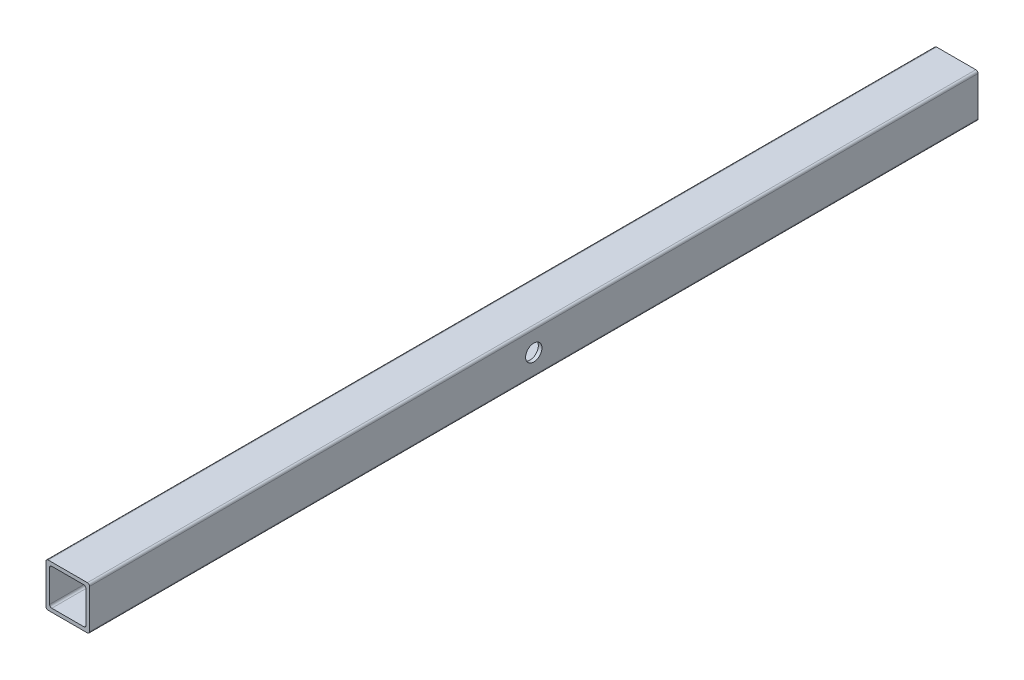
SolidWorks part; units mm, degrees
ref_plane "Front Plane" through (0, 0, 0) normal (0, 0, 1) x (1, 0, 0)
ref_plane "Top Plane" through (0, 0, 0) normal (0, 1, 0) x (1, 0, 0)
ref_plane "Right Plane" through (0, 0, 0) normal (1, 0, 0) x (0, 0, -1)
sketch "Sketch1" plane through (0, 0, 0) normal (0, 0, 1) x (1, 0, 0)
  line L1 (1.27, 0) -> (19.9136, 0)
  line L2 (0, 1.27) -> (0, 19.9136)
  line L3 (1.27, 21.1836) -> (19.9136, 21.1836)
  line L4 (21.1836, 1.27) -> (21.1836, 19.9136)
  line L5 (-0.8382, 23.2918) -> (22.0218, 23.2918)
  line L6 (-2.1082, 22.0218) -> (-2.1082, -0.8382)
  line L7 (-0.8382, -2.1082) -> (22.0218, -2.1082)
  line L8 (23.2918, 22.0218) -> (23.2918, -0.8382)
  arc A0 (19.9136, 0) -> (21.1836, 1.27) centre (19.9136, 1.27) ccw
  arc A1 (22.0218, -2.1082) -> (23.2918, -0.8382) centre (22.0218, -0.8382) ccw
  arc A2 (1.27, 0) -> (0, 1.27) centre (1.27, 1.27) cw
  arc A3 (-2.1082, -0.8382) -> (-0.8382, -2.1082) centre (-0.8382, -0.8382) ccw
  arc A4 (-0.8382, 23.2918) -> (-2.1082, 22.0218) centre (-0.8382, 22.0218) ccw
  arc A5 (22.0218, 23.2918) -> (23.2918, 22.0218) centre (22.0218, 22.0218) cw
  arc A6 (19.9136, 21.1836) -> (21.1836, 19.9136) centre (19.9136, 19.9136) cw
  arc A7 (0, 19.9136) -> (1.27, 21.1836) centre (1.27, 19.9136) cw
  point P14 (23.2918, -2.1082)
  point P17 (0, 0)
  point P22 (-2.1082, 23.2918)
  point P25 (23.2918, 23.2918)
  dimension "D7" = 1.27
  dimension "D1" = 25.4
  dimension "D2" = 25.4
  dimension "D3" = 2.1082
  dimension "D4" = 2.1082
  dimension "D5" = 2.1082
  dimension "D6" = 2.1082
extrude "Boss-Extrude1" add sketch "Sketch1" along normal blind 518.16
sketch "Sketch2" plane through (-2.1082, 0, 0) normal (-1, 0, 0) x (0, 0, 1)
  line L0 (518.16, -2.1082) -> (0, -2.1082) construction
  line L1 (0, 22.0218) -> (0, -0.8382) construction
  line L2 (518.16, 22.0218) -> (518.16, -0.8382) construction
  circle A0 centre (259.08, 10.5918) radius 4.7625
  point P0 (259.08, 10.5918)
  dimension "D3" = 9.525
  dimension "D1" = 12.7
  dimension "D2" = 259.08
extrude "Cut-Extrude1" cut sketch "Sketch2" against normal through all
sketch "Sketch3" [suppressed] plane through (23.2918, 0, 0) normal (1, 0, 0) x (0, 0, -1)
  line L0 (-457.2, 23.2918) -> (0, 23.2918) construction
  line L1 (-457.2, -0.8382) -> (-457.2, 22.0218) construction
  circle A0 centre (-228.6, 10.5918) radius 4.7625
  point P0 (-228.6, 10.5918)
  point P5 (-457.2, 10.5918)
  dimension "D3" = 9.525
  dimension "D1" = 12.7
  dimension "D2" = 228.6
extrude "Cut-Extrude2" [suppressed] cut sketch "Sketch3" against normal through all
sketch "Sketch4" [suppressed] plane through (-2.1082, 0, 0) normal (-1, 0, 0) x (0, 0, 1)
  circle A0 centre (8.1071, 10.5204) radius 4.7625
  circle A1 centre (1339.7256, 10.5204) radius 4.7625
  point P0 (8.1071, 10.5204)
  dimension "D1" = 9.525
  dimension "D2" = 9.525
extrude "Cut-Extrude3" [suppressed] cut sketch "Sketch4" against normal through all
sketch "Sketch5" [suppressed] plane through (0, 23.2918, 0) normal (0, 1, 0) x (1, 0, 0)
  circle A0 centre (10.9617, -1275.6722) radius 4.7625
  circle A1 centre (10.9617, -6.719) radius 4.7625
  dimension "D1" = 9.525
  dimension "D2" = 9.525
extrude "Cut-Extrude4" [suppressed] cut sketch "Sketch5" against normal through all
